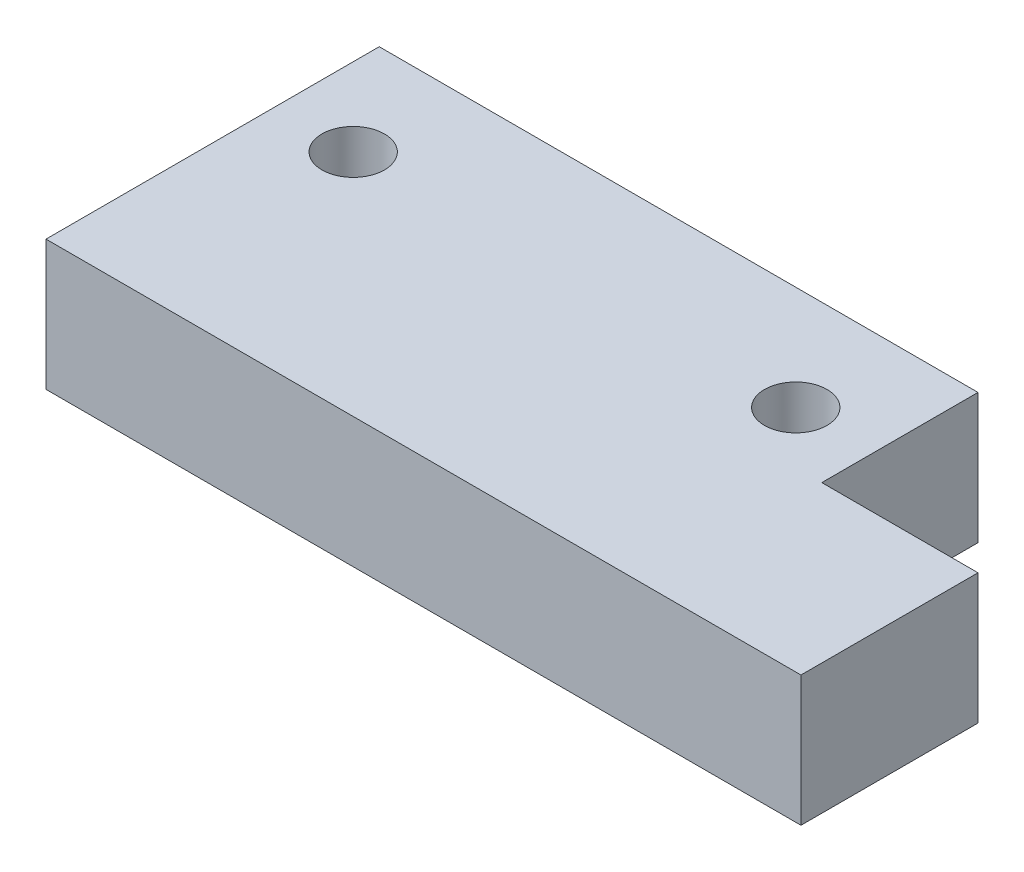
SolidWorks part; units mm, degrees
ref_plane "前基準面" through (0, 0, 0) normal (0, 0, 1) x (1, 0, 0)
ref_plane "上基準面" through (0, 0, 0) normal (0, 1, 0) x (1, 0, 0)
ref_plane "右基準面" through (0, 0, 0) normal (1, 0, 0) x (0, 0, -1)
sketch "草圖1" plane through (0, 0, 0) normal (0, 1, 0) x (1, 0, 0)
  line L1 (0, 0) -> (35, 0)
  line L2 (0, 0) -> (0, 20)
  line L3 (0, 20) -> (35, 20)
  line L4 (35, 0) -> (35, 20)
  dimension "D1" = 35
  dimension "D2" = 20
extrude "填料-伸長1" add sketch "草圖1" along normal blind 5
sketch "草圖3" plane through (0, 0, 0) normal (0, 1, 0) x (1, 0, 0)
  line L1 (6, 0) -> (35, 0)
  line L2 (6, 0) -> (6, 7.2)
  line L3 (6, 7.2) -> (35, 7.2)
  line L4 (35, 0) -> (35, 7.2)
  dimension "D1" = 29
  dimension "D2" = 7.2
extrude "除料-伸長4" cut sketch "草圖3" along normal blind 5
sketch "草圖4" plane through (0, 0, 0) normal (0, 1, 0) x (1, 0, 0)
  line L1 (35, 20) -> (29, 20)
  line L2 (35, 20) -> (35, 14)
  line L3 (35, 14) -> (29, 14)
  line L4 (29, 20) -> (29, 14)
  dimension "D1" = 6
  dimension "D2" = 6
extrude "除料-伸長5" cut sketch "草圖4" along normal blind 5
sketch "草圖5" plane through (0, 0, 0) normal (0, 1, 0) x (1, 0, 0)
  circle A0 centre (3, 16) radius 1.2
  circle A1 centre (3, 4) radius 1.2
  circle A2 centre (9, 16) radius 1.2
  circle A4 centre (26, 16) radius 1.2
extrude "除料-伸長6" cut sketch "草圖5" along normal through all
sketch "草圖6" plane through (0, 0, 0) normal (0, 1, 0) x (1, 0, 0)
  circle A1 centre (3, 16) radius 2.2
  circle A2 centre (3, 4) radius 2.2
extrude "除料-伸長7" cut sketch "草圖6" along normal blind 2
sketch "草圖7" plane through (0, 0, 0) normal (0, 1, 0) x (1, 0, 0)
  circle A0 centre (9, 16) radius 2.2
  circle A1 centre (26, 16) radius 2.2
extrude "除料-伸長8" cut sketch "草圖7" against normal blind 3 from surface at 5 starting at face at (9, 5, -14.8)
mirror "鏡射1" about plane through (0, 0, 0) normal (0, 1, 0) of "除料-伸長8", "除料-伸長7", "除料-伸長5", "除料-伸長4", "填料-伸長1", "除料-伸長6"
sketch "草圖8" plane through (0, 0, 0) normal (0, 1, 0) x (1, 0, 0)
  line L1 (-1.3087, 21.0021) -> (38.9593, 21.0021)
  line L2 (-1.3087, 21.0021) -> (-1.3087, -3.7525)
  line L3 (-1.3087, -3.7525) -> (38.9593, -3.7525)
  line L4 (38.9593, 21.0021) -> (38.9593, -3.7525)
extrude "除料-伸長9" cut sketch "草圖8" along normal through all
sketch "草圖11" plane through (0, 0, 0) normal (0, 1, 0) x (1, 0, 0)
  line L1 (6, 0) -> (0, 0)
  line L2 (6, 0) -> (6, 20)
  line L3 (6, 20) -> (0, 20)
  line L4 (0, 0) -> (0, 20)
extrude "除料-伸長11" cut sketch "草圖11" against normal through all
